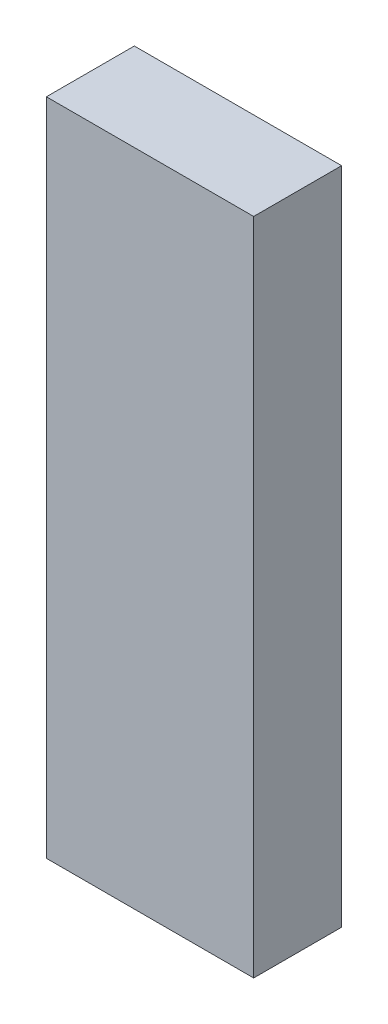
SolidWorks part; units mm, degrees
ref_plane "Front Plane" through (0, 0, 0) normal (0, 0, 1) x (1, 0, 0)
ref_plane "Top Plane" through (0, 0, 0) normal (0, 1, 0) x (1, 0, 0)
ref_plane "Right Plane" through (0, 0, 0) normal (1, 0, 0) x (0, 0, -1)
sketch "Sketch1" plane through (0, 0, 0) normal (0, 0, 1) x (1, 0, 0)
  line L1 (0, 0) -> (33, 0)
  line L2 (0, 0) -> (0, 105)
  line L3 (0, 105) -> (33, 105)
  line L4 (33, 0) -> (33, 105)
  dimension "D1" = 105
  dimension "D2" = 33
extrude "Boss-Extrude1" add sketch "Sketch1" along normal blind 14
